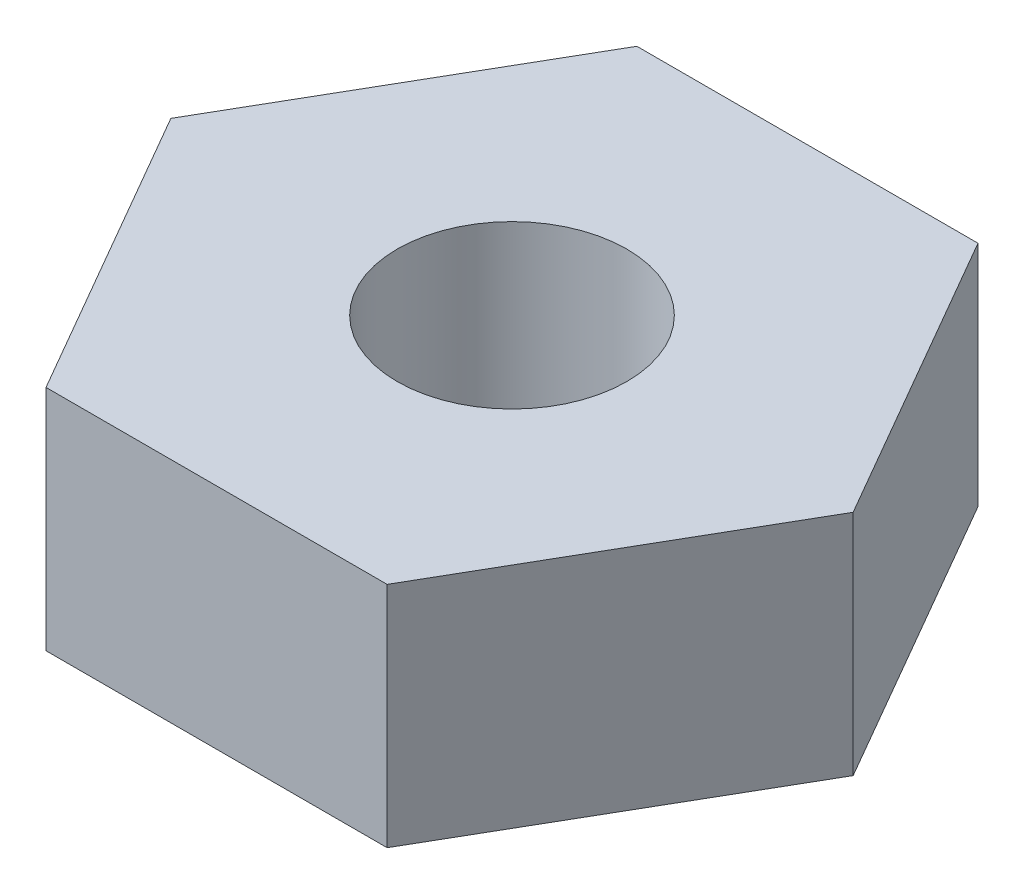
SolidWorks part; units mm, degrees
ref_plane "Front Plane" through (0, 0, 0) normal (0, 0, 1) x (1, 0, 0)
ref_plane "Top Plane" through (0, 0, 0) normal (0, 1, 0) x (1, 0, 0)
ref_plane "Right Plane" through (0, 0, 0) normal (1, 0, 0) x (0, 0, -1)
sketch "Sketch1" plane through (0, 0, 0) normal (0, 1, 0) x (1, 0, 0)
  line L1 (2.2286, 0) -> (1.1143, 1.93)
  line L2 (1.1143, 1.93) -> (-1.1143, 1.93)
  line L3 (-1.1143, 1.93) -> (-2.2286, 0)
  line L4 (-2.2286, 0) -> (-1.1143, -1.93)
  line L5 (-1.1143, -1.93) -> (1.1143, -1.93)
  line L6 (1.1143, -1.93) -> (2.2286, 0)
  circle A0 centre (0, 0) radius 1.93 construction
  circle A1 centre (0, 0) radius 0.75
  dimension "D2" = 1.5
  dimension "D1" = 3.86
extrude "Boss-Extrude1" add sketch "Sketch1" along normal blind 1.49
